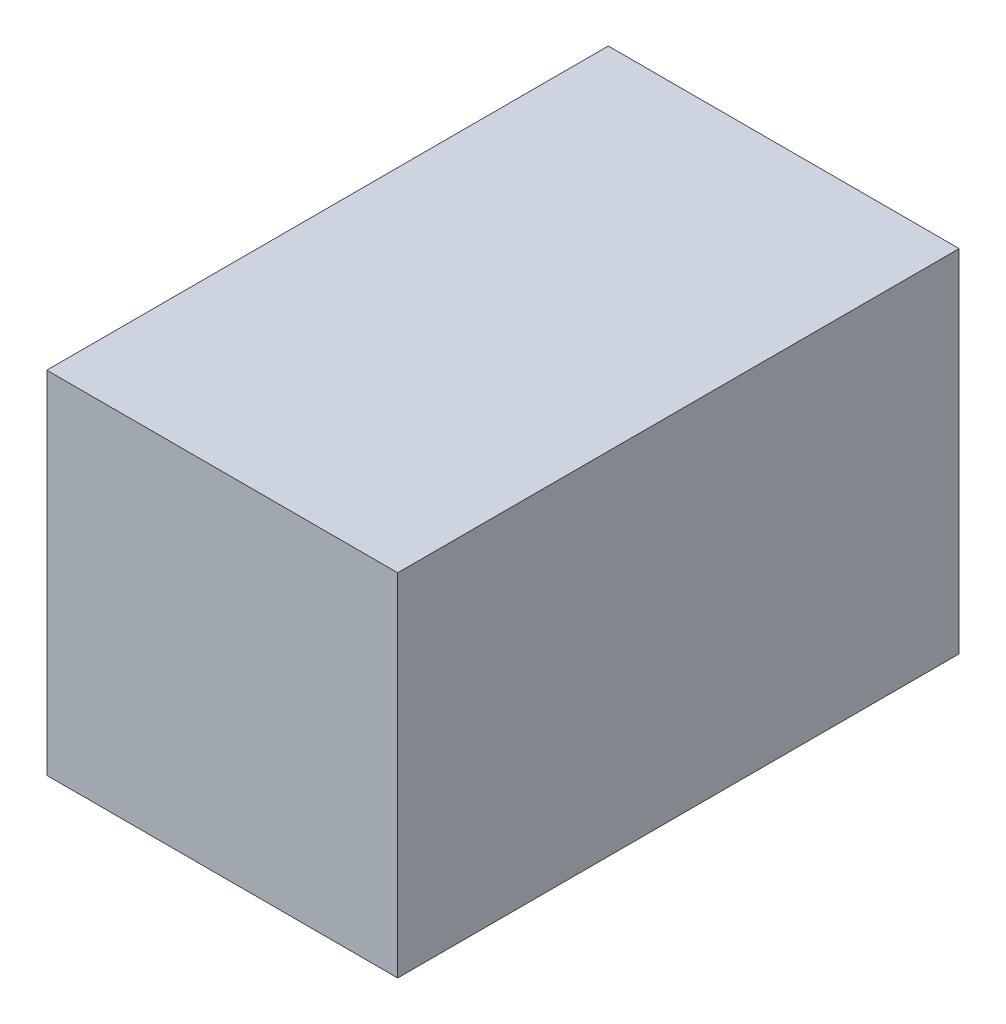
SolidWorks part; units mm, degrees
ref_plane "Front Plane" through (0, 0, 0) normal (0, 0, 1) x (1, 0, 0)
ref_plane "Top Plane" through (0, 0, 0) normal (0, 1, 0) x (1, 0, 0)
ref_plane "Right Plane" through (0, 0, 0) normal (1, 0, 0) x (0, 0, -1)
sketch "Sketch1" plane through (0, 0, 0) normal (0, 0, 1) x (1, 0, 0)
  line L1 (-762, -762) -> (762, -762)
  line L2 (-762, -762) -> (-762, 762)
  line L3 (-762, 762) -> (762, 762)
  line L4 (762, -762) -> (762, 762)
  line L5 (-762, -762) -> (762, 762) construction
  line L6 (-762, 762) -> (762, -762) construction
  point P0 (0, 0)
  dimension "D1" = 1524
extrude " Illuminance Plane 2-12-2019 5:16:28 PM" add sketch "Sketch1" along normal mid plane 2438.4
equation "\"xy\"=1524"
equation "\"D1@Sketch1\"=\"xy\""
equation "\"height\"=2438.4"
equation "\"D1@ Illuminance Plane 2-12-2019 5:16:28 PM\"=\"height\""
